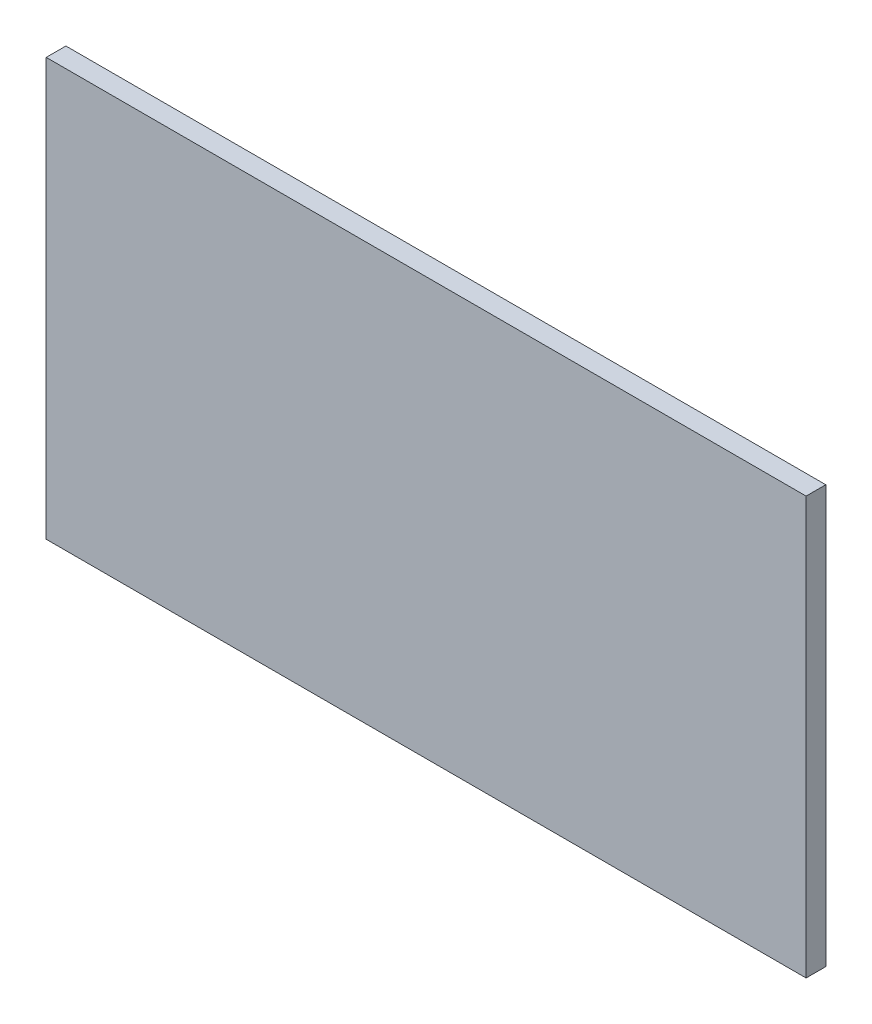
SolidWorks part; units mm, degrees
ref_plane "Plan de face" through (0, 0, 0) normal (0, 0, 1) x (1, 0, 0)
ref_plane "Plan de dessus" through (0, 0, 0) normal (0, 1, 0) x (1, 0, 0)
ref_plane "Plan de droite" through (0, 0, 0) normal (1, 0, 0) x (0, 0, -1)
sketch "Esquisse1" plane through (0, 0, 0) normal (0, 0, 1) x (1, 0, 0)
  line L1 (0, 0) -> (579, 0)
  line L2 (0, 0) -> (0, 318)
  line L3 (0, 318) -> (579, 318)
  line L4 (579, 0) -> (579, 318)
  dimension "D1" = 318
  dimension "D2" = 579
extrude "Boss.-Extru.1" add sketch "Esquisse1" along normal blind 15
